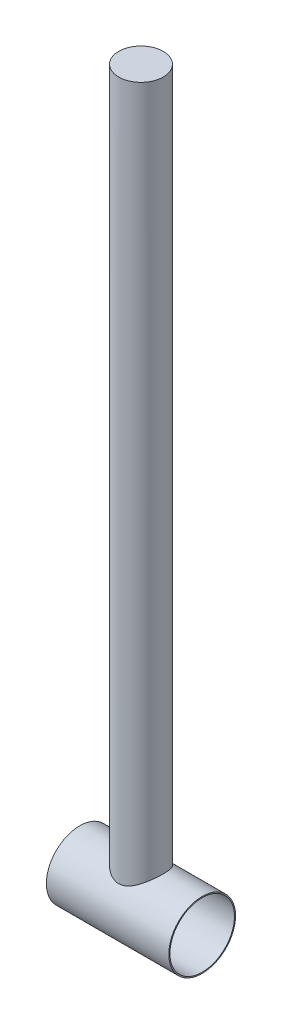
SolidWorks part; units mm, degrees
material "Chrome Stainless Steel"
ref_plane "Plano frontal" through (0, 0, 0) normal (0, 0, 1) x (1, 0, 0)
ref_plane "Plano superior" through (0, 0, 0) normal (0, 1, 0) x (1, 0, 0)
ref_plane "Plano direito" through (0, 0, 0) normal (1, 0, 0) x (0, 0, -1)
sketch "Sketch2" plane through (0, 0, 0) normal (1, 0, 0) x (0, 0, -1)
  circle A0 centre (0, 0) radius 30
  circle A1 centre (0, 0) radius 29
  dimension "D1" = 60
  dimension "D2" = 1
extrude "Boss-Extrude3" add sketch "Sketch2" along normal mid plane 110
sketch "Sketch1" plane through (0, 0, 0) normal (0, 1, 0) x (1, 0, 0)
  circle A0 centre (0, 0) radius 20
  dimension "D1" = 40
extrude "Boss-Extrude4" add sketch "Sketch1" against normal up to surface (627.6393 mm away) from offset 650
